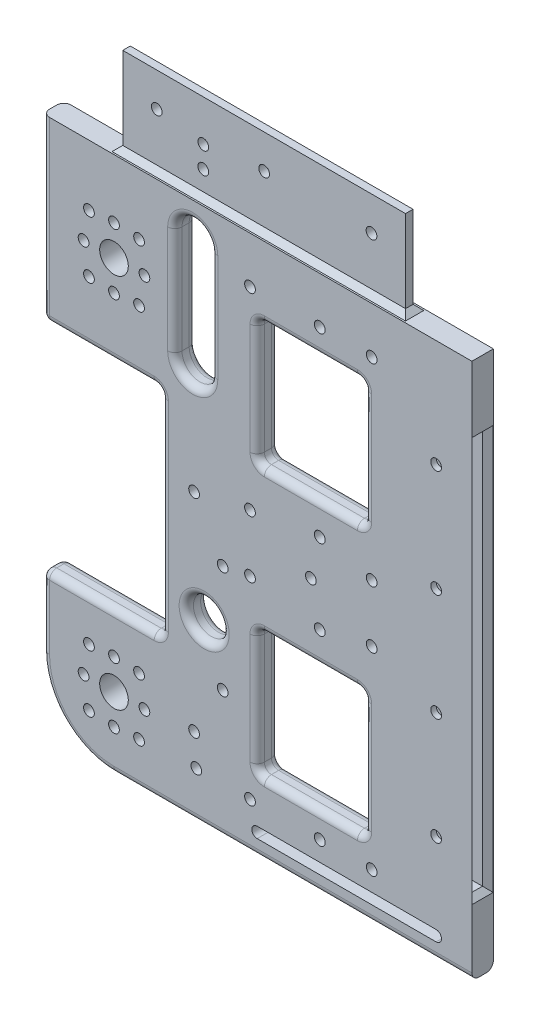
SolidWorks part; units mm, degrees
ref_plane "前视基准面" through (0, 0, 0) normal (0, 0, 1) x (1, 0, 0)
ref_plane "上视基准面" through (0, 0, 0) normal (0, 1, 0) x (1, 0, 0)
ref_plane "右视基准面" through (0, 0, 0) normal (1, 0, 0) x (0, 0, -1)
sketch "草图1" plane through (0, 0, 0) normal (0, 0, 1) x (1, 0, 0)
  line L1 (-60, 75) -> (60, 75)
  line L2 (-60, 75) -> (-60, -75)
  line L3 (-60, -75) -> (60, -75)
  line L4 (60, 75) -> (60, -75)
  line L5 (-60, 75) -> (60, -75) construction
  line L6 (-60, -75) -> (60, 75) construction
  point P0 (0, 0)
  dimension "D1" = 150
  dimension "D2" = 120
extrude "主板" add sketch "草图1" along normal mid plane 6
sketch "草图3" plane through (60, 0, 0) normal (1, 0, 0) x (0, 0, -1)
  line L1 (-1.45, 55) -> (1.45, 55)
  line L2 (-1.45, 55) -> (-1.45, -55)
  line L3 (-1.45, -55) -> (1.45, -55)
  line L4 (1.45, 55) -> (1.45, -55)
  line L5 (-1.45, 55) -> (1.45, -55) construction
  line L6 (-1.45, -55) -> (1.45, 55) construction
  point P0 (0, 0)
  dimension "D1" = 110
  dimension "D2" = 2.9
extrude "右插口" cut sketch "草图3" against normal blind 20
sketch "草图4" plane through (0, 75, 0) normal (0, 1, 0) x (1, 0, 0)
  line L1 (-39.5, 1.05) -> (39.5, 1.05)
  line L2 (-39.5, 1.05) -> (-39.5, -1.05)
  line L3 (-39.5, -1.05) -> (39.5, -1.05)
  line L4 (39.5, 1.05) -> (39.5, -1.05)
  line L5 (-39.5, 1.05) -> (39.5, -1.05) construction
  line L6 (-39.5, -1.05) -> (39.5, 1.05) construction
  point P0 (0, 0)
  dimension "D1" = 79
  dimension "D2" = 2.1
extrude "上插口" add sketch "草图4" along normal blind 24.5
sketch "草图5" plane through (0, 0, 3) normal (0, 0, 1) x (1, 0, 0)
  line L1 (-60, 25) -> (-26.8, 25)
  line L2 (-60, 25) -> (-60, -35)
  line L3 (-60, -35) -> (-26.8, -35)
  line L4 (-26.8, 25) -> (-26.8, -35)
  line L5 (60, 75) -> (-60, 75) construction
  line L6 (-60, -75) -> (60, -75) construction
  line L7 (-60, 75) -> (-60, -75) construction
  dimension "D1" = 50
  dimension "D2" = 40
  dimension "D3" = 0
  dimension "D4" = 33.2
extrude "左轮毂" cut sketch "草图5" against normal blind 10
sketch "草图7" plane through (0, 0, 3) normal (0, 0, 1) x (1, 0, 0)
  line L0 (60, -75) -> (60, 75) construction
  line L1 (60, 75) -> (-60, 75) construction
  line L2 (40, -55) -> (60, -55) construction
  circle A0 centre (50, 45) radius 1.5
  circle A1 centre (50, 15) radius 1.5
  circle A2 centre (50, -15) radius 1.5
  circle A3 centre (50, -45) radius 1.5
  dimension "D1" = 10
  dimension "D2" = 10
  dimension "D3" = 10
  dimension "D4" = 10
  dimension "D5" = 30
  dimension "D6" = 30
  dimension "D7" = 30
  dimension "D8" = 30
  dimension "D9" = 10
extrude "右插孔" cut sketch "草图7" against normal blind 10
sketch "草图6" plane through (0, 0, 1.05) normal (0, 0, 1) x (1, 0, 0)
  line L0 (-39.5, 99.5) -> (39.5, 99.5) construction
  line L1 (-39.5, 99.5) -> (-39.5, 75) construction
  line L2 (39.5, 99.5) -> (39.5, 75) construction
  line L3 (60, 75) -> (-60, 75) construction
  circle A0 centre (-30, 90) radius 1.5
  circle A1 centre (0, 90) radius 1.5
  circle A2 centre (30, 90) radius 1.5
  dimension "D1" = 9.5
  dimension "D2" = 9.5
  dimension "D3" = 9.5
  dimension "D4" = 9.5
  dimension "D5" = 9.5
  dimension "D6" = 30
  dimension "D7" = 15
extrude "上插孔" cut sketch "草图6" against normal blind 10
sketch "草图8" plane through (0, 0, 3) normal (0, 0, 1) x (1, 0, 0)
  line L0 (60, 75) -> (-60, 75) construction
  line L1 (60, -75) -> (60, 75) construction
  line L2 (-60, -75) -> (60, -75) construction
  circle A0 centre (17.5, 62) radius 1.5
  circle A1 centre (17.5, 11.2) radius 1.5
  circle A2 centre (17.5, -11.2) radius 1.5
  circle A3 centre (17.5, -62) radius 1.5
  dimension "D1" = 13
  dimension "D2" = 42.5
  dimension "D3" = 50.8
  dimension "D4" = 0
  dimension "D5" = 0
  dimension "D6" = 0
  dimension "D7" = 50.8
  dimension "D8" = 13
extrude "驱动板" cut sketch "草图8" against normal blind 10
sketch "草图9" plane through (0, 0, 3) normal (0, 0, 1) x (1, 0, 0)
  line L0 (60, 75) -> (-60, 75) construction
  line L1 (60, -75) -> (60, 75) construction
  line L2 (-60, -75) -> (60, -75) construction
  circle A0 centre (-2, 62) radius 1.5
  circle A1 centre (32, -62) radius 1.5
  circle A2 centre (32, 62) radius 1.5
  circle A3 centre (-2, -62) radius 1.5
  circle A4 centre (-2, 8) radius 1.5
  circle A5 centre (-2, -8) radius 1.5
  circle A6 centre (32, 8) radius 1.5
  circle A7 centre (32, -8) radius 1.5
  dimension "D1" = 13
  dimension "D5" = 54
  dimension "D2" = 62
  dimension "D3" = 28
  dimension "D4" = 13
  dimension "D6" = 54
  dimension "D7" = 0
  dimension "D8" = 54
  dimension "D9" = 54
  dimension "D10" = 34
  dimension "D11" = 34
  dimension "D12" = 34
  dimension "D13" = 34
extrude "稳压板" cut sketch "草图9" against normal blind 10
sketch "草图14" plane through (0, 0, 3) normal (0, 0, 1) x (1, 0, 0)
  line L0 (-60, -35) -> (-26.8, -35) construction
  line L1 (-26.8, -35) -> (-26.8, 25) construction
  circle A0 centre (-17.62, -53.4) radius 1.5
  circle A1 centre (-17.62, 4.6) radius 1.5
  circle A2 centre (-9.62, -9.4) radius 1.5
  circle A3 centre (-9.62, -39.4) radius 1.5
  dimension "D1" = 4.4
  dimension "D2" = 17.18
  dimension "D3" = 17.18
  dimension "D4" = 8
  dimension "D5" = 8
  dimension "D6" = 14
  dimension "D7" = 30
  dimension "D8" = 14
extrude "左电机" cut sketch "草图14" against normal blind 10
sketch "草图15" plane through (0, 0, 3) normal (0, 0, 1) x (1, 0, 0)
  line L0 (-39.5, 75) -> (39.5, 75) construction
  line L1 (-60, 75) -> (-60, 25) construction
  line L2 (60, 75) -> (-60, 75) construction
  line L4 (-23, 65) -> (-13, 65)
  line L5 (-23, 65) -> (-23, 35)
  line L6 (-23, 35) -> (-13, 35)
  line L7 (-13, 65) -> (-13, 35)
  circle A0 centre (-18, 35) radius 5
  circle A1 centre (-18, 65) radius 5
  dimension "D1" = 40
  dimension "D3" = 10
  dimension "D4" = 42
  dimension "D2" = 42
extrude "过线孔" cut sketch "草图15" against normal blind 10 contours L4 A1 | L4 A1 | A1 L5 A0 L7 | L6 A0 | L6 A0
sketch "草图16" plane through (0, 0, 3) normal (0, 0, 1) x (1, 0, 0)
  line L0 (60, 75) -> (-60, 75) construction
  line L1 (0, 55) -> (30, 55)
  line L2 (0, 55) -> (0, 20)
  line L3 (0, 20) -> (30, 20)
  line L4 (30, 55) -> (30, 20)
  line L5 (0, -20) -> (30, -20)
  line L6 (0, -20) -> (0, -55)
  line L7 (0, -55) -> (30, -55)
  line L8 (30, -20) -> (30, -55)
  line L9 (60, -75) -> (60, 75) construction
  line L10 (-60, -75) -> (60, -75) construction
  line L11 (-26.8, -35) -> (-26.8, 25) construction
  line L12 (-60, -35) -> (-26.8, -35) construction
  circle A0 centre (-14.8, -25) radius 5
  dimension "D9" = 12
  dimension "D1" = 20
  dimension "D2" = 30
  dimension "D3" = 35
  dimension "D4" = 30
  dimension "D5" = 20
  dimension "D6" = 30
  dimension "D7" = 35
  dimension "D8" = 30
  dimension "D10" = 10
extrude "减重孔" cut sketch "草图16" against normal blind 10
sketch "草图10" plane through (0, 0, 3) normal (0, 0, 1) x (1, 0, 0)
  line L0 (60, 75) -> (-60, 75) construction
  line L1 (-60, 75) -> (-60, 25) construction
  circle A0 centre (-40, 50) radius 4
  circle A1 centre (-33, 58) radius 1.5
  circle A2 centre (-47, 58) radius 1.5
  circle A3 centre (-47, 42) radius 1.5
  circle A4 centre (-33, 42) radius 1.5
  circle A5 centre (-31.5, 50) radius 1.5
  circle A6 centre (-48.5, 50) radius 1.5
  circle A7 centre (-40, 58.5) radius 1.5
  circle A8 centre (-40, 41.5) radius 1.5
  dimension "D1" = 25
  dimension "D2" = 20
  dimension "D3" = 8.5
  dimension "D4" = 0
  dimension "D5" = 0
  dimension "D6" = 0
  dimension "D7" = 0
  dimension "D8" = 8.5
  dimension "D9" = 8.5
  dimension "D10" = 8.5
  dimension "D11" = 8
  dimension "D12" = 8
  dimension "D13" = 7
  dimension "D14" = 7
  dimension "D15" = 8
  dimension "D16" = 8
  dimension "D17" = 7
  dimension "D18" = 7
extrude "垂直板1" cut sketch "草图10" against normal blind 10
sketch "草图11" plane through (0, 0, 3) normal (0, 0, 1) x (1, 0, 0)
  line L0 (-60, -35) -> (-60, -75) construction
  line L1 (-60, -75) -> (60, -75) construction
  circle A0 centre (-40, -55) radius 4
  circle A1 centre (-40, -46.5) radius 1.5
  circle A2 centre (-31.5, -55) radius 1.5
  circle A3 centre (-40, -63.5) radius 1.5
  circle A4 centre (-48.5, -55) radius 1.5
  circle A5 centre (-33, -63) radius 1.5
  circle A6 centre (-47, -63) radius 1.5
  circle A7 centre (-47, -47) radius 1.5
  circle A8 centre (-33, -47) radius 1.5
  dimension "D1" = 20
  dimension "D3" = 8.5
  dimension "D2" = 20
  dimension "D4" = 8.5
  dimension "D5" = 8.5
  dimension "D6" = 8.5
  dimension "D7" = 8
  dimension "D8" = 8
  dimension "D9" = 8
  dimension "D10" = 8
  dimension "D11" = 7
  dimension "D12" = 7
  dimension "D13" = 7
  dimension "D14" = 7
extrude "垂直板2" cut sketch "草图11" against normal blind 10
sketch "草图13" plane through (0, 0, 1.05) normal (0, 0, 1) x (1, 0, 0)
  line L0 (-39.5, 75) -> (39.5, 75) construction
  line L1 (-39.5, 99.5) -> (-39.5, 75) construction
  line L2 (-60, 75) -> (-60, 25) construction
  circle A0 centre (-17, 88) radius 1.5
  circle A1 centre (-17, 82) radius 1.5
  dimension "D1" = 7
  dimension "D2" = 13
  dimension "D3" = 22.5
  dimension "D4" = 22.5
  dimension "D5" = 43
  dimension "D6" = 43
extrude "二层板1" cut sketch "草图13" against normal blind 10
sketch "草图12" plane through (0, 0, 3) normal (0, 0, 1) x (1, 0, 0)
  line L0 (-60, -75) -> (60, -75) construction
  line L1 (60, -75) -> (60, 75) construction
  circle A0 centre (-17, -62) radius 1.5
  dimension "D1" = 13
  dimension "D2" = 77
extrude "二层板2" cut sketch "草图12" against normal blind 10
sketch "草图18" plane through (0, 0, 3) normal (0, 0, 1) x (1, 0, 0)
  line L0 (60, -75) -> (60, 75) construction
  line L1 (60, 75) -> (-60, 75) construction
  circle A0 centre (15, 0) radius 1.5
  dimension "D1" = 45
  dimension "D2" = 75
extrude "底架" cut sketch "草图18" against normal blind 10
chamfer "右倒角" distance 1.5 angle 45 4 edges at (60, -55, 0) (60, 0, 1.45) (60, 0, -1.45) (60, 55, 0)
chamfer "上倒角" distance 1.5 angle 45 4 edges at (39.5, 75, 0) (0, 75, -1.05) (-39.5, 75, 0) (0, 75, 1.05)
fillet "左下大圆角" radius 20 1 edges at (-60, -75, 0)
fillet "减重孔圆角" radius 2 26 edges at (0, -37.5, -3) (0, -37.5, 3) (15, -20, -3) (0, -20, 0) (15, -20, 3) (30, -37.5, -3) (30, -20, 0) (30, -37.5, 3) (15, -55, -3) (30, -55, 0) (15, -55, 3) (0, -55, 0) (0, 37.5, -3) (0, 37.5, 3) (15, 55, -3) (0, 55, 0) (15, 55, 3) (30, 37.5, -3) (30, 55, 0) (30, 37.5, 3) (15, 20, -3) (30, 20, 0) (15, 20, 3) (0, 20, 0) (-9.8, -25, -3) (-9.8, -25, 3)
fillet "过线孔圆角" radius 2 8 edges at (-18, 70, -3) (-18, 70, 3) (-13, 50, 3) (-13, 50, -3) (-18, 30, -3) (-18, 30, 3) (-23, 50, -3) (-23, 50, 3)
fillet "边缘圆角" radius 2 18 edges at (10, -75, -3) (10, -75, 3) (-54.1421, -69.1421, -3) (-54.1421, -69.1421, 3) (-60, -45, -3) (-60, -45, 3) (-60, 50, -3) (-60, 50, 3) (-43.4, -35, -3) (-43.4, -35, 3) (-60, -35, 0) (-26.8, -5, -3) (-26.8, -5, 3) (-26.8, -35, 0) (-43.4, 25, -3) (-60, 25, 0) (-43.4, 25, 3) (-26.8, 25, 0)
sketch "草图19" plane through (0, 0, 3) normal (0, 0, 1) x (1, 0, 0)
  line L0 (60, -73) -> (60, 75) construction
  line L1 (60, -75) -> (-40, -75) construction
  line L3 (0, -67.5) -> (50, -67.5)
  line L4 (0, -67.5) -> (0, -70.5)
  line L5 (0, -70.5) -> (50, -70.5)
  line L6 (50, -67.5) -> (50, -70.5)
  circle A0 centre (50, -69) radius 1.5
  circle A1 centre (0, -69) radius 1.5
  dimension "D1" = 10
  dimension "D2" = 6
  dimension "D3" = 6
  dimension "D4" = 60
extrude "尾寻迹" cut sketch "草图19" against normal blind 10 contours L4 A1 | A1 L5 A0 L3 | L4 A1 | L6 A0
sketch "电机过线" plane through (0, 0, 3) normal (0, 0, 1) x (1, 0, 0)
  line L0 (-26.8, -33) -> (-26.8, 23) construction
  line L1 (8.2, -25) -> (23.2, -25)
  line L2 (8.2, -25) -> (8.2, -50)
  line L3 (8.2, -50) -> (23.2, -50)
  line L4 (23.2, -25) -> (23.2, -50)
  line L5 (-58, -35) -> (-28.8, -35) construction
  dimension "D1" = 35
  dimension "D2" = 15
  dimension "D3" = 25
  dimension "D4" = 15
